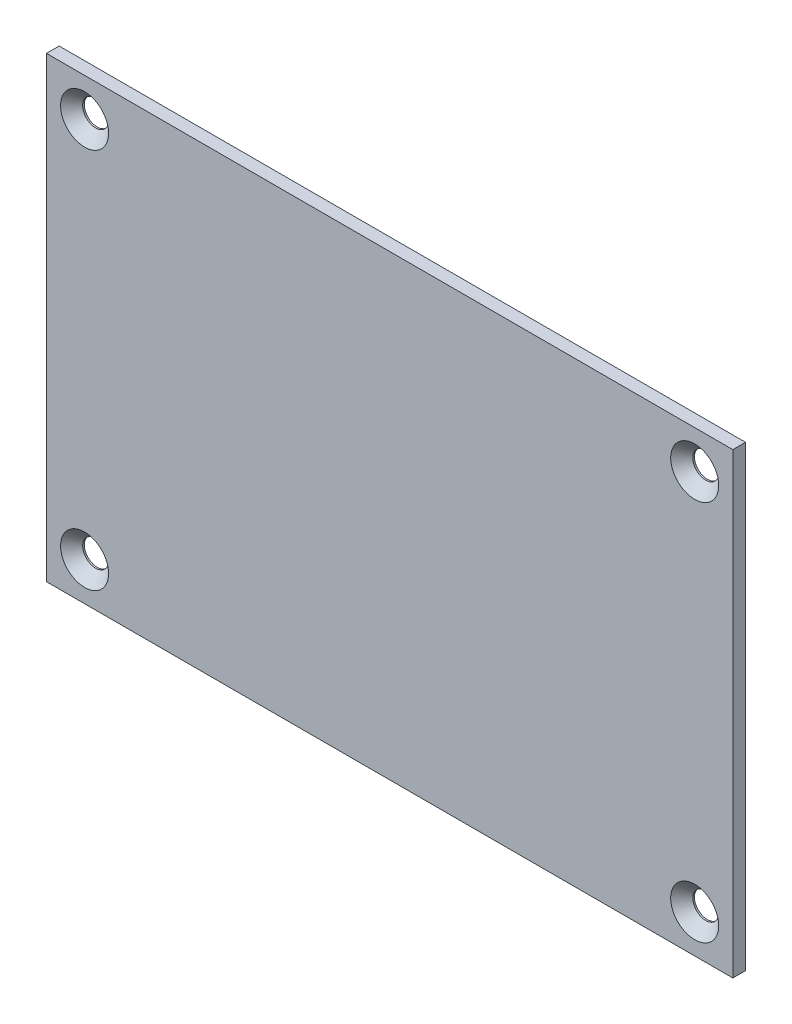
SolidWorks part; units mm, degrees
ref_plane "Front Plane" through (0, 0, 0) normal (0, 0, 1) x (1, 0, 0)
ref_plane "Top Plane" through (0, 0, 0) normal (0, 1, 0) x (1, 0, 0)
ref_plane "Right Plane" through (0, 0, 0) normal (1, 0, 0) x (0, 0, -1)
sketch "Sketch1" plane through (0, 0, 0) normal (0, 0, 1) x (1, 0, 0)
  line L1 (0, 0) -> (90, 0)
  line L2 (0, 0) -> (0, 60)
  line L3 (0, 60) -> (90, 60)
  line L4 (90, 0) -> (90, 60)
  dimension "D1" = 60
  dimension "D2" = 90
extrude "Boss-Extrude1" add sketch "Sketch1" along normal blind 1.666
sketch "Sketch3" plane through (0, 0, 1.666) normal (0, 0, 1) x (1, 0, 0)
  line L8 (5, 55) -> (5, 5)
  line L9 (5, 5) -> (85, 5)
  line L10 (85, 5) -> (85, 55)
  line L11 (85, 55) -> (5, 55)
  line L12 (5, 55) -> (5, 5)
  line L13 (5, 5) -> (85, 5)
  line L14 (85, 5) -> (85, 55)
  line L15 (85, 55) -> (5, 55)
  point P6 (5, 55)
  point P8 (5, 5)
  point P10 (85, 5)
  point P11 (85, 55)
  dimension "D1" = 5
hole_wizard "CSK for M3 Countersunk Flat Head Screw1" positions "Sketch3" profile "Sketch4" countersink size "M3" standard "ISO"
sketch "Sketch4" plane through (5, 55, 1.666) normal (1, 0, 0) x (0, -1, 0)
  line L0 (0, 0) -> (0, 31.0215)
  line L1 (0, 31.0215) -> (1.7, 30)
  line L2 (1.7, 30) -> (1.7, 1.45)
  line L3 (1.7, 1.45) -> (3.15, 0)
  line L5 (3.15, 0) -> (0, 0)
  line L6 (-1.7, 1.45) -> (-3.15, 0) construction
  line L10 (0, 31.0215) -> (-1.7, 30) construction
  line L11 (0, -6.35) -> (0, 107.95) construction
  dimension "Hole Dia." = 3.4
  dimension "Hole Depth" = 30
  dimension "Near C'Sink Dia." = 6.3
  dimension "Near C'Sink Angle" = 90
  dimension "Drill Angle" = 118
